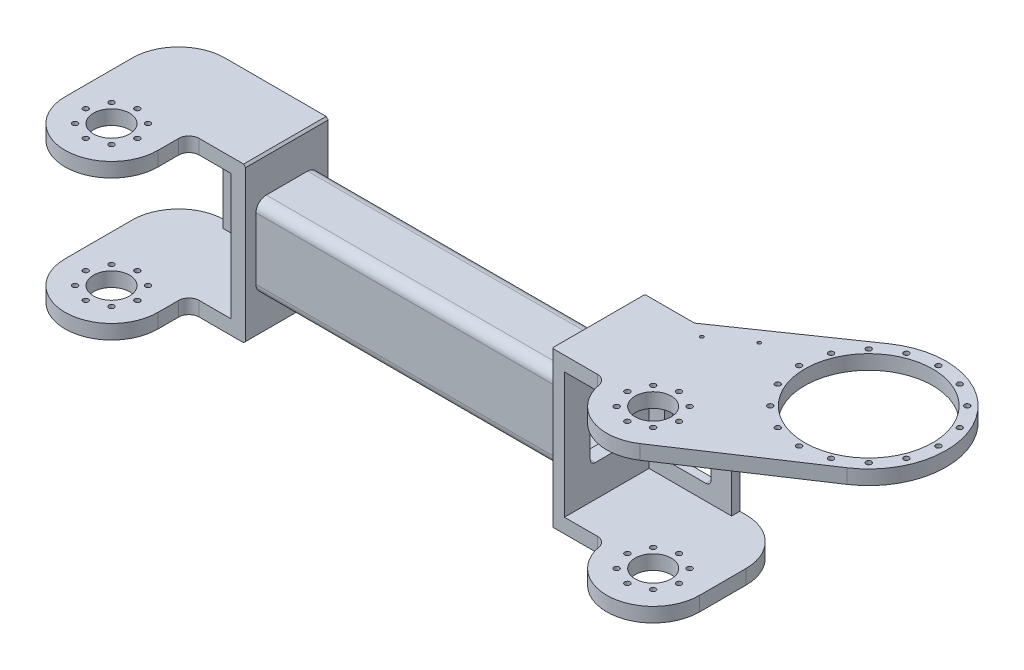
SolidWorks part; units mm, degrees
material "Q235"
ref_plane "Front" through (0, 0, 0) normal (0, 0, 1) x (1, 0, 0)
ref_plane "Top" through (0, 0, 0) normal (0, 1, 0) x (1, 0, 0)
ref_plane "Right" through (0, 0, 0) normal (1, 0, 0) x (0, 0, -1)
sketch "草图1" plane through (0, 0, 0) normal (0, 1, 0) x (1, 0, 0)
  line L0 (-100, 40) -> (0, 40)
  line L1 (0, 40) -> (0, -40)
  line L2 (0, -40) -> (-45, -40)
  line L3 (-145, -70) -> (-145, -5)
  line L4 (0, 0) -> (-100, 0) construction
  line L5 (-100, 0) -> (-100, -70) construction
  line L6 (-55, -70) -> (-55, -50)
  arc A0 (-55, -70) -> (-145, -70) centre (-100, -70) cw
  arc A1 (-45, -40) -> (-55, -50) centre (-45, -50) ccw
  arc A2 (-100, 40) -> (-145, -5) centre (-100, -5) ccw
  point P5 (0, 0)
  dimension "D2" = 100
  dimension "D5" = 10
  dimension "D6" = 45
  dimension "D3" = 70
  dimension "D1" = 80
  dimension "D4" = 145
extrude "凸台-拉伸1" add sketch "草图1" along normal mid plane 150
sketch "草图2" plane through (0, 0, 40) normal (0, 0, 1) x (1, 0, 0)
  line L1 (-314, 61) -> (-14, 61)
  line L2 (-314, 61) -> (-314, -61)
  line L3 (-314, -61) -> (-14, -61)
  line L4 (-14, 61) -> (-14, -61)
  line L6 (0, 75) -> (0, -75) construction
  point P4 (0, 0)
  dimension "D1" = 122
  dimension "D2" = 61
  dimension "D3" = 14
  dimension "D4" = 300
extrude "切除-拉伸1" cut sketch "草图2" against normal mid plane 200
sketch "草图3" plane through (0, 75, 0) normal (0, 1, 0) x (1, 0, 0)
  line L0 (0, 0) -> (-100, 0) construction
  line L1 (0, -40) -> (0, 40) construction
  line L2 (-100, 0) -> (-100, -70) construction
  circle A0 centre (-100, -70) radius 17.5
  dimension "D1" = 35
  dimension "D2" = 100
  dimension "D3" = 70
extrude "切除-拉伸2" cut sketch "草图3" against normal blind 240
sketch "草图4" plane through (0, -75, 0) normal (0, -1, 0) x (1, 0, 0)
  circle A0 centre (-100, 70) radius 25 construction
  circle A1 centre (-100, 95) radius 2.55
  circle A2 centre (-117.6777, 87.6777) radius 2.55
  circle A3 centre (-125, 70) radius 2.55
  circle A4 centre (-117.6777, 52.3223) radius 2.55
  circle A5 centre (-100, 45) radius 2.55
  circle A6 centre (-82.3223, 52.3223) radius 2.55
  circle A7 centre (-75, 70) radius 2.55
  circle A8 centre (-82.3223, 87.6777) radius 2.55
  point P22 (-100, 70)
  dimension "D1" = 50
  dimension "D2" = 5.1
  dimension "D3" = 8
extrude "切除-拉伸3" cut sketch "草图4" against normal blind 240
sketch "草图8" plane through (0, 0, 0) normal (0, 1, 0) x (1, 0, 0)
  line L0 (0, 0) -> (300, 0) construction
  line L1 (400, 45) -> (300, 45)
  line L2 (300, 45) -> (300, -45)
  line L3 (300, -45) -> (345.9167, -45)
  line L4 (300, 0) -> (400, 0) construction
  line L5 (400, 0) -> (506.066, -106.066) construction
  line L6 (445, -45) -> (445, 0)
  line L7 (400, 0) -> (400, -45) construction
  arc A0 (445, -45) -> (355.7501, -53.1818) centre (400, -45) cw
  circle A1 centre (506.066, -106.066) radius 100 construction
  arc A2 (445, 0) -> (400, 45) centre (400, 0) ccw
  arc A3 (355.7501, -53.1818) -> (345.9167, -45) centre (345.9167, -55) ccw
  dimension "D1" = 90
  dimension "D5" = 200
  dimension "D7" = 100
  dimension "D8" = 10
  dimension "D3" = 45
  dimension "D2" = 300
  dimension "D4" = 150
  dimension "D6" = 135
extrude "凸台-拉伸4" add sketch "草图8" along normal mid plane 150 separate body
sketch "草图9" plane through (0, 0, 0) normal (1, 0, 0) x (0, 0, -1)
  line L0 (30, 40) -> (-30, -40) construction
  line L1 (-20, 40) -> (20, 40)
  line L2 (-30, 30) -> (-30, -30)
  line L3 (-20, -40) -> (20, -40)
  line L4 (30, 30) -> (30, -30)
  line L5 (0, 0) -> (-30, 0) construction
  line L6 (26, 30) -> (26, -30)
  line L7 (-20, -36) -> (20, -36)
  line L8 (-26, 30) -> (-26, -30)
  line L9 (-20, 36) -> (20, 36)
  arc A0 (20, 40) -> (30, 30) centre (20, 30) cw
  arc A1 (30, -30) -> (20, -40) centre (20, -30) cw
  arc A2 (-20, -40) -> (-30, -30) centre (-20, -30) cw
  arc A3 (-30, 30) -> (-20, 40) centre (-20, 30) cw
  arc A4 (26, -30) -> (20, -36) centre (20, -30) cw
  arc A5 (-20, -36) -> (-26, -30) centre (-20, -30) cw
  arc A6 (-26, 30) -> (-20, 36) centre (-20, 30) cw
  arc A7 (20, 36) -> (26, 30) centre (20, 30) cw
  dimension "D3" = 10
  dimension "D1" = 60
  dimension "D2" = 80
  dimension "D4" = 4
extrude "凸台-拉伸5" add sketch "草图9" along normal up to surface (300 mm away) up to face at (300, 0, 0)
sketch "草图10" plane through (0, 0, 45) normal (0, 0, 1) x (1, 0, 0)
  line L0 (300, 75) -> (300, -75) construction
  line L1 (314, 61) -> (514, 61)
  line L2 (314, 61) -> (314, -61)
  line L3 (314, -61) -> (514, -61)
  line L4 (514, 61) -> (514, -61)
  line L5 (0, 0) -> (381.7242, 0) construction
  dimension "D1" = 122
  dimension "D2" = 14
  dimension "D3" = 61
  dimension "D4" = 200
extrude "切除-拉伸4" cut sketch "草图10" against normal mid plane 200
sketch "草图11" plane through (0, 75, 0) normal (0, 1, 0) x (1, 0, 0)
  line L0 (300, 0) -> (400, 0) construction
  line L1 (300, 45) -> (300, -45) construction
  line L2 (400, 0) -> (400, -45) construction
  circle A0 centre (400, -45) radius 17.5
  dimension "D1" = 35
  dimension "D2" = 100
  dimension "D3" = 45
extrude "切除-拉伸5" cut sketch "草图11" against normal up to surface (150 mm away) up to face at (372.3141, -75, 18.2579)
sketch "草图12" plane through (0, 75, 0) normal (0, 1, 0) x (1, 0, 0)
  circle A0 centre (400, -45) radius 25 construction
  circle A1 centre (375, -45) radius 2.55
  circle A2 centre (382.3223, -62.6777) radius 2.55
  circle A3 centre (400, -70) radius 2.55
  circle A4 centre (417.6777, -62.6777) radius 2.55
  circle A5 centre (425, -45) radius 2.55
  circle A6 centre (417.6777, -27.3223) radius 2.55
  circle A7 centre (400, -20) radius 2.55
  circle A8 centre (382.3223, -27.3223) radius 2.55
  point P21 (400, -45)
  dimension "D1" = 50
  dimension "D2" = 5.1
  dimension "D3" = 8
extrude "切除-拉伸6" cut sketch "草图12" against normal up to surface (150 mm away) up to face at (400, -75, 62.5)
sketch "草图13" plane through (0, 75, 0) normal (0, 1, 0) x (1, 0, 0)
  line L0 (0, 0) -> (400, 0) construction
  line L1 (400, 0) -> (503.923, 60) construction
  line L5 (445, -45) -> (445, 0) construction
  line L6 (400, 45) -> (300, 45) construction
  line L7 (545.4043, -2.4844) -> (424.8888, -82.4906)
  line L8 (445, -45) -> (445, 0)
  line L9 (400, 45) -> (350, 45)
  line L13 (350, 45) -> (461.3609, 121.7532)
  line L14 (300, 45) -> (300, -45) construction
  arc A0 (355.7501, -53.1818) -> (445, -45) centre (400, -45) ccw construction
  arc A1 (424.8888, -82.4906) -> (445, -45) centre (400, -45) ccw
  arc A2 (461.3609, 121.7532) -> (545.4043, -2.4844) centre (503.923, 60) cw
  arc A4 (445, 0) -> (400, 45) centre (400, 0) ccw construction
  arc A5 (445, 0) -> (400, 45) centre (400, 0) ccw
  dimension "D1" = 150
  dimension "D2" = 120
  dimension "D3" = 75
  dimension "D4" = 50
extrude "凸台-拉伸6" add sketch "草图13" against normal up to surface (14 mm away) up to face at (382.3223, 61, 65.2277)
sketch "草图14" plane through (0, 75, 0) normal (0, 1, 0) x (1, 0, 0)
  circle A0 centre (503.923, 60) radius 62
  dimension "D1" = 124
extrude "切除-拉伸7" cut sketch "草图14" against normal blind 14
sketch "草图15" plane through (0, 75, 0) normal (0, 1, 0) x (1, 0, 0)
  circle A0 centre (503.923, 60) radius 67.5 construction
  circle A1 centre (503.923, -7.5) radius 2.55
  circle A2 centre (529.7542, -2.3619) radius 2.55
  circle A3 centre (551.6528, 12.2703) radius 2.55
  circle A4 centre (566.2849, 34.1689) radius 2.55
  circle A5 centre (571.423, 60) radius 2.55
  circle A6 centre (566.2849, 85.8311) radius 2.55
  circle A7 centre (551.6528, 107.7297) radius 2.55
  circle A8 centre (529.7542, 122.3619) radius 2.55
  circle A9 centre (503.923, 127.5) radius 2.55
  circle A10 centre (478.0919, 122.3619) radius 2.55
  circle A11 centre (456.1933, 107.7297) radius 2.55
  circle A12 centre (441.5612, 85.8311) radius 2.55
  circle A13 centre (436.423, 60) radius 2.55
  circle A14 centre (441.5612, 34.1689) radius 2.55
  circle A15 centre (456.1933, 12.2703) radius 2.55
  circle A16 centre (478.0919, -2.3619) radius 2.55
  point P38 (503.923, 60)
  dimension "D1" = 135
  dimension "D2" = 5.1
  dimension "D3" = 16
extrude "切除-拉伸8" cut sketch "草图15" against normal blind 14
sketch "草图16" plane through (-14, 0, 0) normal (-1, 0, 0) x (0, 0, 1)
  line L0 (20, 30) -> (-20, -30) construction
  line L1 (-15, 30) -> (15, 30)
  line L2 (-20, 25) -> (-20, -25)
  line L3 (-15, -30) -> (15, -30)
  line L4 (20, 25) -> (20, -25)
  line L5 (0, 0) -> (20, 0) construction
  line L6 (0, 0) -> (0, -11.7405) construction
  arc A0 (-20, -25) -> (-15, -30) centre (-15, -25) ccw
  arc A1 (15, -30) -> (20, -25) centre (15, -25) ccw
  arc A2 (20, 25) -> (15, 30) centre (15, 25) ccw
  arc A3 (-20, 25) -> (-15, 30) centre (-15, 25) cw
  dimension "D3" = 5
  dimension "D1" = 40
  dimension "D2" = 60
extrude "切除-拉伸9" cut sketch "草图16" against normal up to surface (328 mm away) up to face at (314, 0, 0)
sketch "草图17" plane through (0, 75, 0) normal (0, 1, 0) x (1, 0, 0)
  line L0 (397.9351, 59.8206) -> (365, 37.1208) construction
  line L1 (461.3609, 121.7532) -> (350, 45) construction
  line L2 (300, 45) -> (300, -45) construction
  circle A0 centre (397.9351, 59.8206) radius 1.7
  circle A1 centre (365, 37.1208) radius 1.7
  dimension "D1" = 3.4
  dimension "D2" = 3.4
  dimension "D5" = 65
  dimension "D3" = 40
  dimension "D4" = 15
extrude "切除-拉伸10" cut sketch "草图17" against normal blind 14
sketch "草图18" plane through (314, 0, 0) normal (1, 0, 0) x (0, 0, -1)
  line L0 (45, -61) -> (-45, -61) construction
  line L1 (45, 61) -> (37, 61)
  line L2 (45, 61) -> (45, -61)
  line L3 (45, -61) -> (37, -61)
  line L4 (37, 61) -> (37, -61)
  dimension "D1" = 8
extrude "凸台-拉伸7" add sketch "草图18" along normal blind 80
sketch "草图19" plane through (0, 0, -37) normal (0, 0, 1) x (1, 0, 0)
  line L0 (363.3043, 61) -> (314, 61) construction
  line L1 (334, 46) -> (369, 46)
  line L2 (329, 41) -> (329, -41)
  line L3 (334, -46) -> (369, -46)
  line L4 (374, 41) -> (374, -41)
  line L5 (394, 61) -> (394, -61) construction
  line L6 (394, -61) -> (314, -61) construction
  line L7 (314, 61) -> (314, -61) construction
  arc A0 (369, 46) -> (374, 41) centre (369, 41) cw
  arc A1 (329, -41) -> (334, -46) centre (334, -41) ccw
  arc A2 (369, -46) -> (374, -41) centre (369, -41) ccw
  arc A3 (334, 46) -> (329, 41) centre (334, 41) ccw
  dimension "D5" = 5
  dimension "D1" = 15
  dimension "D2" = 20
  dimension "D3" = 15
  dimension "D4" = 15
extrude "切除-拉伸11" cut sketch "草图19" against normal blind 8
sketch "草图20" plane through (-14, 0, 0) normal (-1, 0, 0) x (0, 0, 1)
  line L0 (-40, -61) -> (40, -61) construction
  line L1 (-40, 61) -> (-32, 61)
  line L2 (-40, 61) -> (-40, -61)
  line L3 (-40, -61) -> (-32, -61)
  line L4 (-32, 61) -> (-32, -61)
  dimension "D1" = 8
extrude "凸台-拉伸8" add sketch "草图20" along normal blind 80
sketch "草图21" plane through (0, 0, -32) normal (0, 0, 1) x (1, 0, 0)
  line L0 (-94, 61) -> (-14, 61) construction
  line L1 (-64, 46) -> (-34, 46)
  line L2 (-74, 36) -> (-74, -36)
  line L3 (-64, -46) -> (-34, -46)
  line L4 (-24, 36) -> (-24, -36)
  line L5 (-14, -61) -> (-14, 61) construction
  line L6 (-94, -61) -> (-94, 61) construction
  line L7 (-94, -61) -> (-14, -61) construction
  arc A0 (-34, 46) -> (-24, 36) centre (-34, 36) cw
  arc A1 (-74, -36) -> (-64, -46) centre (-64, -36) ccw
  arc A2 (-34, -46) -> (-24, -36) centre (-34, -36) ccw
  arc A3 (-64, 46) -> (-74, 36) centre (-64, 36) ccw
  dimension "D5" = 10
  dimension "D1" = 15
  dimension "D2" = 10
  dimension "D3" = 20
  dimension "D4" = 15
extrude "切除-拉伸12" cut sketch "草图21" against normal blind 8
sketch "草图22" plane through (0, 0, -32) normal (0, 0, 1) x (1, 0, 0)
  line L0 (-84, 25) -> (-84, -25) construction
  line L1 (0, 0) -> (-53.9533, 0) construction
  line L2 (-94, -61) -> (-94, 61) construction
  circle A0 centre (-84, 25) radius 1.7
  circle A1 centre (-84, -25) radius 1.7
  dimension "D1" = 3.4
  dimension "D2" = 3.4
  dimension "D4" = 25
  dimension "D3" = 50
  dimension "D5" = 10
extrude "切除-拉伸13" cut sketch "草图22" against normal blind 10
chamfer "倒角1" distance 2 angle 45 4 edges at (300, 75, 0) (300, -75, 0) (0, -75, 0) (0, 75, 0)
sketch "草图23" plane through (0, 0, -37) normal (0, 0, 1) x (1, 0, 0)
  line L0 (384, 25) -> (384, -25) construction
  line L1 (0, 0) -> (359.5176, 0) construction
  line L2 (394, 61) -> (394, -61) construction
  circle A0 centre (384, 25) radius 1.7
  circle A1 centre (384, -25) radius 1.7
  dimension "D1" = 3.4
  dimension "D2" = 3.4
  dimension "D4" = 25
  dimension "D3" = 50
  dimension "D5" = 10
extrude "切除-拉伸14" cut sketch "草图23" against normal blind 10
chamfer "倒角2" distance 3 angle 45 2 edges at (300, 0, -45) (300, 0, 45)
sketch "草图24" plane through (0, 75, 0) normal (0, 1, 0) x (1, 0, 0)
  line L0 (503.923, 60) -> (400, -45)
  line L1 (400, -45) -> (-100, -70)
  line L2 (-100, -70) -> (503.923, 60)
  circle A0 centre (400, -45) radius 17.5 construction
  circle A1 centre (400, -45) radius 17.5
  circle A2 centre (-100, -70) radius 17.5 construction
  circle A3 centre (-100, -70) radius 17.5
  circle A4 centre (503.923, 60) radius 62 construction
  circle A5 centre (503.923, 60) radius 62
  dimension "D1" = 137.567
